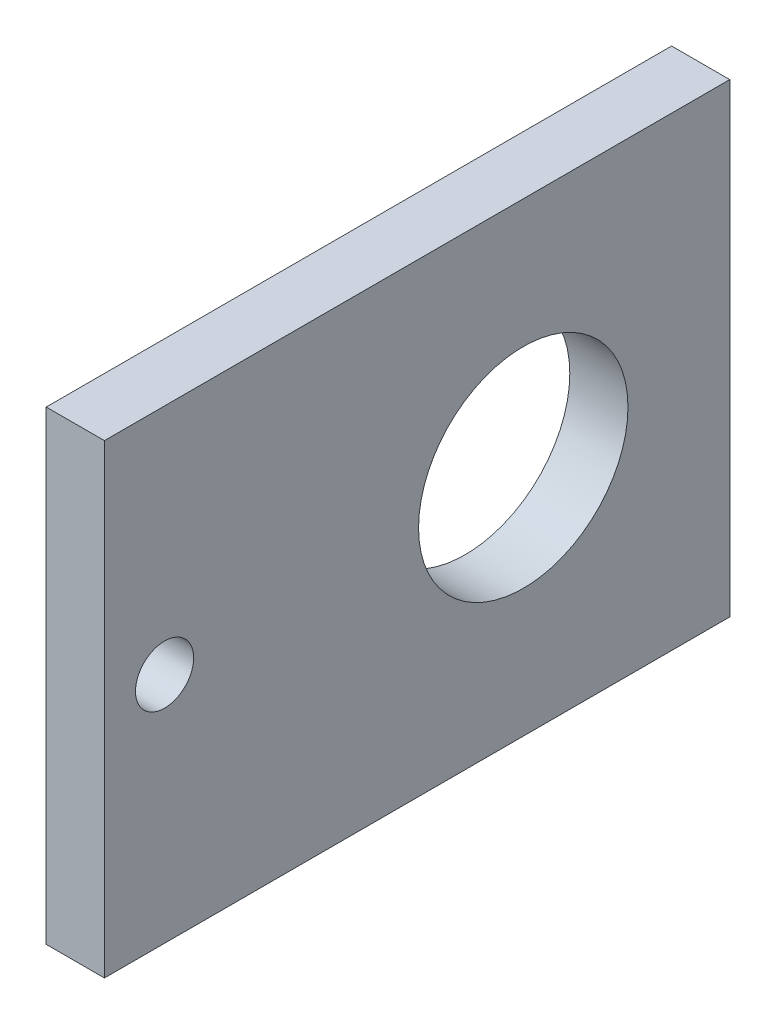
SolidWorks part; units mm, degrees
ref_plane "Front Plane" through (0, 0, 0) normal (0, 0, 1) x (1, 0, 0)
ref_plane "Top Plane" through (0, 0, 0) normal (0, 1, 0) x (1, 0, 0)
ref_plane "Right Plane" through (0, 0, 0) normal (1, 0, 0) x (0, 0, -1)
sketch "Sketch1" plane through (0, 0, 0) normal (1, 0, 0) x (0, 0, -1)
  line L1 (0, 0) -> (53.7472, 0)
  line L2 (0, 0) -> (0, -40)
  line L3 (0, -40) -> (53.7472, -40)
  line L6 (52, 0) -> (60.882, -17.7639) construction
  line L7 (52, 240) -> (52, -360) construction
  line L8 (53.7472, 0) -> (53.7472, -40)
  line L9 (28.1326, -15.6292) -> (43.8674, -24.3708) construction
  circle A0 centre (36, -20) radius 9
  circle A1 centre (5.1691, -20) radius 2.5
  dimension "D3" = 18
  dimension "D1" = 5
  dimension "D2" = 40
extrude "Boss-Extrude1" add sketch "Sketch1" along normal blind 5
